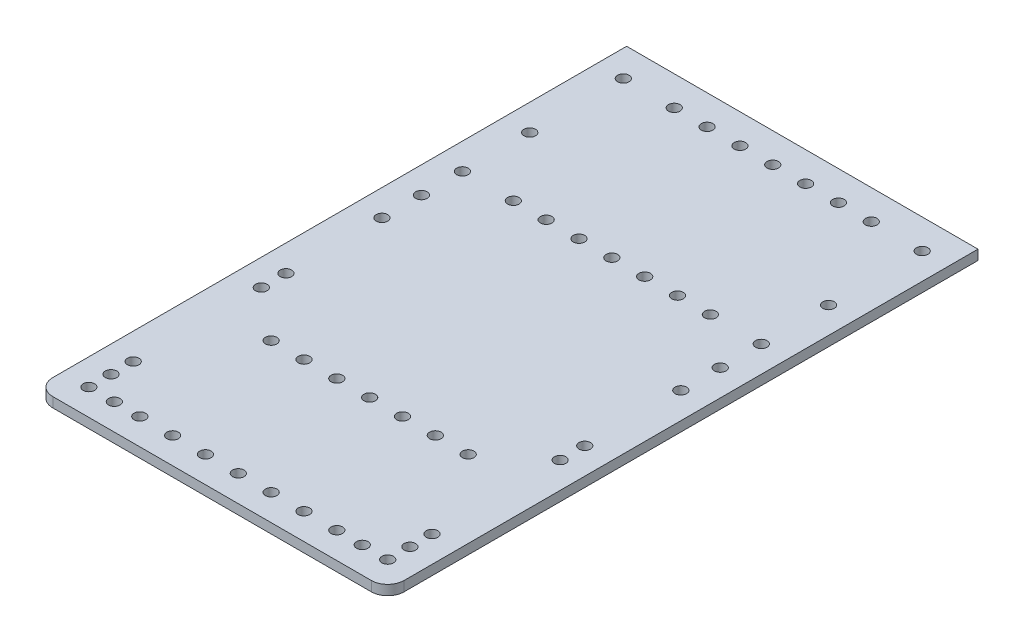
SolidWorks part; units mm, degrees
ref_plane "Front Plane" through (0, 0, 0) normal (0, 0, 1) x (1, 0, 0)
ref_plane "Top Plane" through (0, 0, 0) normal (0, 1, 0) x (1, 0, 0)
ref_plane "Right Plane" through (0, 0, 0) normal (1, 0, 0) x (0, 0, -1)
sketch "Sketch1" plane through (0, 0, 0) normal (0, 1, 0) x (1, 0, 0)
  line L0 (-40.8658, -37.5214) -> (66.1342, -37.5214)
  line L1 (-40.8658, -37.5214) -> (-40.8658, 142.2286)
  line L2 (-40.8658, 142.2286) -> (66.1342, 142.2286)
  line L3 (66.1342, 142.2286) -> (66.1342, -37.5214)
  line L4 (-40.8658, -37.5214) -> (-40.8658, -22.7714)
  line L5 (-40.8658, -37.5214) -> (-32.8658, -37.5214)
  circle A0 centre (-32.8658, -22.7714) radius 1.75
  circle A1 centre (-32.8658, 59.7286) radius 1.75
  circle A3 centre (-32.8658, -29.5214) radius 1.75
  circle A5 centre (-32.8658, -16.0214) radius 1.75
  circle A6 centre (-32.8658, 22.9786) radius 1.75
  circle A7 centre (-32.8658, 30.4786) radius 1.75
  circle A9 centre (-32.8658, 71.7286) radius 1.75
  circle A10 centre (-32.8658, 84.2286) radius 1.75
  circle A11 centre (-32.8658, 104.7286) radius 1.75
  circle A16 centre (12.6342, 84.2286) radius 1.75
  circle A17 centre (2.6342, 84.2286) radius 1.75
  circle A18 centre (-7.3658, 84.2286) radius 1.75
  circle A19 centre (-17.3658, 84.2286) radius 1.75
  circle A21 centre (-25.1158, -29.5214) radius 1.75
  circle A22 centre (-17.3658, -29.5214) radius 1.75
  circle A23 centre (-7.3658, -29.5214) radius 1.75
  circle A24 centre (2.6342, -29.5214) radius 1.75
  circle A25 centre (12.6342, -29.5214) radius 1.75
  circle A26 centre (-17.3658, 10.4786) radius 1.75
  circle A27 centre (-7.3658, 10.4786) radius 1.75
  circle A28 centre (2.6342, 10.4786) radius 1.75
  circle A29 centre (12.6342, 10.4786) radius 1.75
  circle A30 centre (2.6342, 133.2286) radius 1.75
  circle A31 centre (-7.3658, 133.2286) radius 1.75
  circle A32 centre (12.6342, 133.2286) radius 1.75
  circle A33 centre (-32.8658, 133.2286) radius 1.75
  circle A34 centre (-17.3658, 133.2286) radius 1.75
  circle A35 centre (42.6342, 133.2286) radius 1.75
  circle A36 centre (58.1342, 133.2286) radius 1.75
  circle A37 centre (32.6342, 133.2286) radius 1.75
  circle A38 centre (22.6342, 133.2286) radius 1.75
  circle A39 centre (22.6342, 10.4786) radius 1.75
  circle A40 centre (32.6342, 10.4786) radius 1.75
  circle A41 centre (42.6342, 10.4786) radius 1.75
  circle A42 centre (22.6342, -29.5214) radius 1.75
  circle A43 centre (32.6342, -29.5214) radius 1.75
  circle A44 centre (42.6342, -29.5214) radius 1.75
  circle A45 centre (50.3842, -29.5214) radius 1.75
  circle A46 centre (42.6342, 84.2286) radius 1.75
  circle A47 centre (32.6342, 84.2286) radius 1.75
  circle A48 centre (22.6342, 84.2286) radius 1.75
  circle A49 centre (58.1342, 104.7286) radius 1.75
  circle A50 centre (58.1342, 84.2286) radius 1.75
  circle A51 centre (58.1342, 71.7286) radius 1.75
  circle A52 centre (58.1342, 30.4786) radius 1.75
  circle A53 centre (58.1342, 22.9786) radius 1.75
  circle A54 centre (58.1342, -16.0214) radius 1.75
  circle A55 centre (58.1342, -29.5214) radius 1.75
  circle A56 centre (58.1342, 59.7286) radius 1.75
  circle A57 centre (58.1342, -22.7714) radius 1.75
extrude "Boss-Extrude1" add sketch "Sketch1" along normal blind 3 contours L3 L2 L1 L0 A56 A54 A52 A50 A45 A43 A41 A39 A38 A37 A34 A33 A31 A19 A17 A0 A1 A3 A5 A6 A7 A9
fillet "Fillet1" radius 5 2 edges at (66.1342, 1.5, 37.5214) (-40.8658, 1.5, 37.5214)
